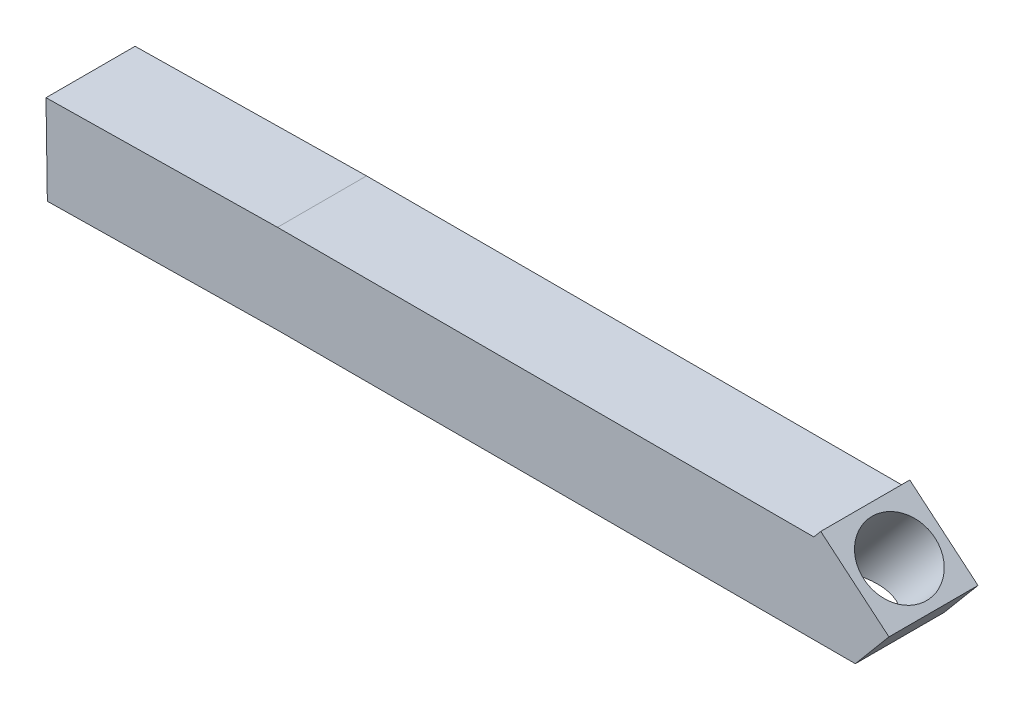
SolidWorks part; units mm, degrees
ref_plane "Front Plane" through (0, 0, 0) normal (0, 0, 1) x (1, 0, 0)
ref_plane "Top Plane" through (0, 0, 0) normal (0, 1, 0) x (1, 0, 0)
ref_plane "Right Plane" through (0, 0, 0) normal (1, 0, 0) x (0, 0, -1)
sketch "Sketch1" plane through (0, 0, 0) normal (0, 0, 1) x (1, 0, 0)
  line L0 (-70.4062, -77.7101) -> (-55.3505, -77.7101)
  line L1 (-55.3505, -77.7101) -> (-55.1558, -77.478)
  line L2 (-70.4062, -77.7101) -> (-70.3683, -80.2098)
  line L3 (-70.3683, -80.2098) -> (-54.1845, -80.2098)
  line L4 (-54.1845, -80.2098) -> (-53.2406, -79.0849)
  line L5 (-53.2406, -79.0849) -> (-55.1558, -77.478)
  line L6 (11.1852, 4.1139) -> (9.5873, 2.2096) construction
  line L7 (11.1852, 4.1139) -> (11.1852, 7.0792) construction
  line L8 (-70.4062, -77.7101) -> (-70.3683, -80.2098) construction
  ellipse E0 centre (11.2008, 4.132) end of major axis (10.4443, 4.786) minor radius 0.024 construction
  dimension "D4" = 2.5
  dimension "D5" = 2.5
  dimension "D6" = 2.4858
  dimension "D7" = 140
extrude "Boss-Extrude1" add sketch "Sketch1" along normal blind 2.5
sketch "Sketch2" plane through (-60.9395, -72.6249, 0) normal (0.6428, 0.766, 0) x (0, 0, -1)
  line L0 (-2.5, -10.0501) -> (-2.5, -7.5501) construction
  circle A0 centre (-1.25, -8.8001) radius 1
  point P4 (-2.5, -8.8001)
  dimension "D1" = 2
extrude "Cut-Extrude1" cut sketch "Sketch2" against normal blind 4.5
sketch "Sketch3" plane through (-71.5657, -1.0829, 0) normal (-0.9999, -0.0151, 0) x (0, 0, 1)
  line L0 (0, -76.6359) -> (0, -79.1359) construction
  line L1 (2.5, -79.1359) -> (0, -79.1359) construction
  circle A0 centre (1.25, -77.8859) radius 1
  point P4 (0, -77.8859)
  point P7 (1.25, -79.1359)
  dimension "D1" = 2
extrude "Cut-Extrude2" cut sketch "Sketch3" against normal blind 9.5
sketch "Sketch5" plane through (-71.5657, -1.0829, 0) normal (-0.9999, -0.0151, 0) x (0, 0, 1)
  line L0 (0, -77.8859) -> (2.5, -77.8859) construction
  line L1 (0, -76.6359) -> (0, -79.1359) construction
  line L2 (2.5, -76.6359) -> (2.5, -79.1359) construction
  line L3 (1.25, -76.6359) -> (1.25, -79.1359) construction
  line L4 (2.5, -76.6359) -> (0, -76.6359) construction
  line L5 (2.5, -79.1359) -> (0, -79.1359) construction
  circle A0 centre (1.25, -77.8859) radius 1
extrude "Boss-Extrude2" add sketch "Sketch5" against normal blind 9.5
sketch "Sketch6" plane through (-71.5657, -1.0829, 0) normal (-0.9999, -0.0151, 0) x (0, 0, 1)
  line L0 (0, -76.6359) -> (2.5, -76.6359)
  line L1 (0, -76.6359) -> (0, -79.1359)
  line L2 (2.5, -76.6359) -> (2.5, -79.1359)
  line L3 (0, -79.1359) -> (2.5, -79.1359)
  line L4 (2.5, -79.1359) -> (0, -79.1359) construction
  dimension "D1" = 0
sketch "Sketch7" plane through (-71.5657, -1.0829, 0) normal (-0.9999, -0.0151, 0) x (0, 0, 1)
  line L0 (0, -76.6359) -> (2.5, -76.6359)
  line L1 (0, -76.6359) -> (0, -79.1229)
  line L2 (2.5, -76.6359) -> (2.5, -79.1229)
  line L3 (0, -79.1229) -> (2.5, -79.1229)
extrude "Boss-Extrude5" add sketch "Sketch7" along normal blind 17
sketch "Sketch8" plane through (-88.5637, -1.3401, 0) normal (-0.9999, -0.0151, 0) x (0, 0, 1)
  line L0 (0, -77.8859) -> (2.5, -77.8859) construction
  line L1 (0, -76.6359) -> (0, -79.1359) construction
  line L2 (2.5, -76.6359) -> (2.5, -79.1359) construction
  line L3 (1.25, -76.6359) -> (1.25, -79.1359) construction
  line L4 (0, -76.6359) -> (2.5, -76.6359) construction
  line L5 (0, -79.1359) -> (2.5, -79.1359) construction
  circle A0 centre (1.25, -77.8859) radius 1
  dimension "D1" = 2
extrude "Cut-Extrude3" cut sketch "Sketch8" against normal blind 9.5
sketch "Sketch9" plane through (-88.5637, -1.3401, 0) normal (-0.9999, -0.0151, 0) x (0, 0, 1)
  line L0 (0, -76.6359) -> (2.5, -76.6359)
  line L1 (0, -76.6359) -> (0, -79.1468)
  line L2 (2.5, -76.6359) -> (2.5, -79.1468)
  line L3 (0, -79.1468) -> (2.5, -79.1468)
extrude "Cut-Extrude4" cut sketch "Sketch9" against normal blind 10.5
sketch "Sketch10" plane through (-78.0649, -1.1813, 0) normal (-0.9999, -0.0151, 0) x (0, 0, 1)
  line L0 (0, -77.8859) -> (2.5, -77.8859) construction
  line L1 (0, -76.6359) -> (0, -79.1359) construction
  line L2 (2.5, -76.6359) -> (2.5, -79.1359) construction
  line L3 (1.25, -76.6359) -> (1.25, -79.1359) construction
  line L4 (0, -76.6359) -> (2.5, -76.6359) construction
  line L5 (0, -79.1359) -> (2.5, -79.1359) construction
  circle A0 centre (1.25, -77.8859) radius 1
  dimension "D1" = 2
extrude "Cut-Extrude5" cut sketch "Sketch10" against normal blind 4.5
sketch "Sketch11" plane through (-78.0649, -1.1813, 0) normal (-0.9999, -0.0151, 0) x (0, 0, 1)
  line L0 (0, -77.8859) -> (2.5, -77.8859) construction
  line L1 (0, -76.6359) -> (0, -79.1359) construction
  line L2 (2.5, -76.6359) -> (2.5, -79.1359) construction
  line L3 (1.25, -76.6359) -> (1.25, -79.1359) construction
  line L4 (0, -76.6359) -> (2.5, -76.6359) construction
  line L5 (0, -79.1359) -> (2.5, -79.1359) construction
  circle A0 centre (1.25, -77.8859) radius 1
extrude "Boss-Extrude6" add sketch "Sketch11" against normal blind 4.5
sketch "Sketch12" plane through (-78.0649, -1.1813, 0) normal (-0.9999, -0.0151, 0) x (0, 0, 1)
  line L0 (0, -77.8859) -> (2.5, -77.8859) construction
  line L1 (0, -76.6359) -> (0, -79.1359) construction
  line L2 (2.5, -76.6359) -> (2.5, -79.1359) construction
  line L3 (1.25, -76.6359) -> (1.25, -79.1359) construction
  line L4 (0, -76.6359) -> (2.5, -76.6359) construction
  line L5 (0, -79.1359) -> (2.5, -79.1359) construction
  circle A0 centre (1.25, -77.8859) radius 1
  dimension "D1" = 2
extrude "Cut-Extrude6" cut sketch "Sketch12" against normal blind 4
sketch "Sketch13" plane through (-78.0649, -1.1813, 0) normal (-0.9999, -0.0151, 0) x (0, 0, 1)
  line L3 (0, -76.6359) -> (2.5, -76.6359)
  line L4 (0, -76.6359) -> (0, -79.1359)
  line L5 (0, -79.1359) -> (2.5, -79.1359)
  line L6 (2.5, -76.6359) -> (2.5, -79.1359)
extrude "Cut-Extrude7" cut sketch "Sketch13" against normal up to vertex (6.5 mm away) up to point (-70.4062, -77.7101, 0)
sketch "Sketch14" plane through (-71.5657, -1.0829, 0) normal (-0.9999, -0.0151, 0) x (0, 0, 1)
  line L1 (0, -76.6359) -> (2.5, -76.6359)
  line L2 (0, -76.6359) -> (0, -79.1359)
  line L3 (0, -79.1359) -> (2.5, -79.1359)
  line L4 (2.5, -76.6359) -> (2.5, -79.1359)
extrude "Boss-Extrude7" add sketch "Sketch14" along normal blind 6.5
sketch "Sketch15" plane through (-78.0649, -1.1813, 0) normal (-0.9999, -0.0151, 0) x (0, 0, 1)
  line L0 (0, -77.8859) -> (2.5, -77.8859) construction
  line L1 (0, -76.6359) -> (0, -79.1359) construction
  line L2 (2.5, -76.6359) -> (2.5, -79.1359) construction
  line L3 (1.25, -76.6359) -> (1.25, -79.1359) construction
  line L4 (0, -76.6359) -> (2.5, -76.6359) construction
  line L5 (0, -79.1359) -> (2.5, -79.1359) construction
  circle A0 centre (1.25, -77.8859) radius 1
  dimension "D1" = 2
extrude "Cut-Extrude8" cut sketch "Sketch15" against normal blind 5
